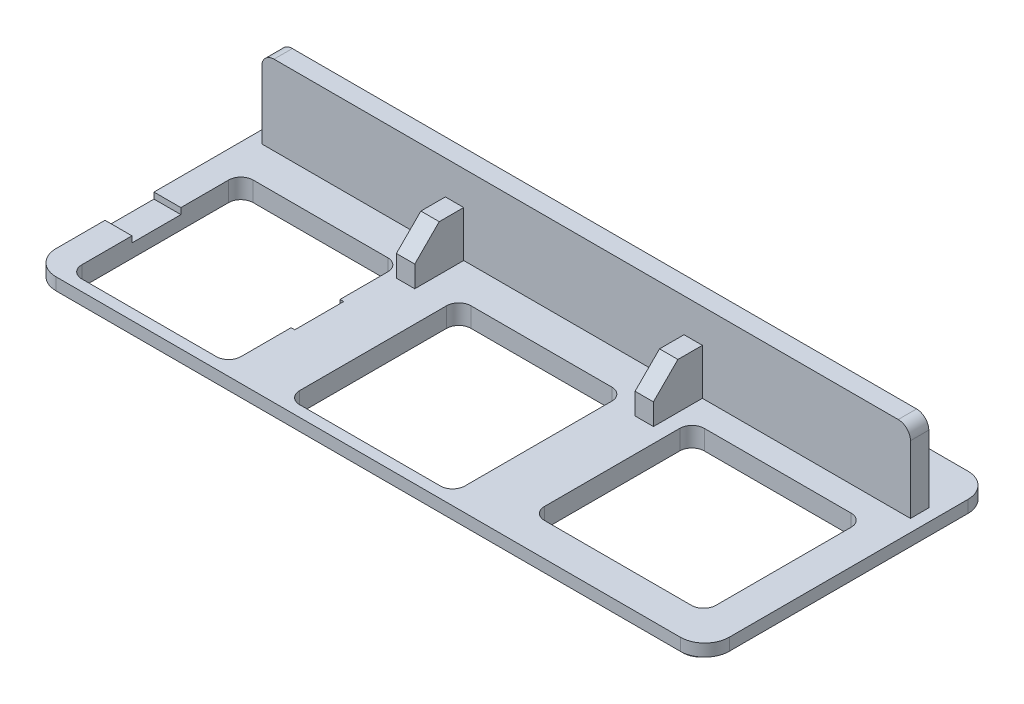
SolidWorks part; units mm, degrees
ref_plane "前视基准面" through (0, 0, 0) normal (0, 0, 1) x (1, 0, 0)
ref_plane "上视基准面" through (0, 0, 0) normal (0, 1, 0) x (1, 0, 0)
ref_plane "右视基准面" through (0, 0, 0) normal (1, 0, 0) x (0, 0, -1)
sketch "草图1" plane through (0, 0, 0) normal (0, 1, 0) x (1, 0, 0)
  line L1 (-27.5, 11.75) -> (27.5, 11.75)
  line L2 (-27.5, 11.75) -> (-27.5, -11.75)
  line L3 (-27.5, -11.75) -> (27.5, -11.75)
  line L4 (27.5, 11.75) -> (27.5, -11.75)
  line L5 (-27.5, 11.75) -> (27.5, -11.75) construction
  line L6 (-27.5, -11.75) -> (27.5, 11.75) construction
  point P0 (0, 0)
  dimension "D1" = 23.5
  dimension "D2" = 55
extrude "凸台-拉伸1" add sketch "草图1" along normal blind 1
fillet "圆角1" radius 2 4 edges at (-27.5, 0.5, 11.75) (27.5, 0.5, 11.75) (-27.5, 0.5, -11.75) (27.5, 0.5, -11.75)
sketch "草图2" plane through (0, 0, 0) normal (0, -1, 0) x (1, 0, 0)
  line L0 (-27.5, -9.75) -> (-27.5, 9.75) construction
  line L1 (-26.6, 11.15) -> (26.6, 11.15)
  line L2 (-26.6, 11.15) -> (-26.6, -11.15)
  line L3 (-26.6, -11.15) -> (26.6, -11.15)
  line L4 (26.6, 11.15) -> (26.6, -11.15)
  line L5 (27.5, 9.75) -> (27.5, -9.75) construction
  line L6 (-25.5, 11.75) -> (25.5, 11.75) construction
  line L7 (25.5, -11.75) -> (-25.5, -11.75) construction
  dimension "D1" = 0.9
  dimension "D2" = 0.9
  dimension "D3" = 0.6
  dimension "D4" = 0.6
extrude "凸台-拉伸2" add sketch "草图2" along normal blind 0.6
sketch "草图3" plane through (0, -0.6, 0) normal (0, -1, 0) x (1, 0, 0)
  line L1 (-25.3, 10.85) -> (-12.3, 10.85)
  line L2 (-25.3, 10.85) -> (-25.3, -3.15)
  line L3 (-25.3, -3.15) -> (-12.3, -3.15)
  line L4 (-12.3, 10.85) -> (-12.3, -3.15)
  line L5 (-7.5, 10.85) -> (6, 10.85)
  line L6 (-7.5, 10.85) -> (-7.5, -3.15)
  line L7 (-7.5, -3.15) -> (6, -3.15)
  line L8 (6, 10.85) -> (6, -3.15)
  line L9 (10.7, 9.0414) -> (24.7, 9.0414)
  line L10 (10.7, 9.0414) -> (10.7, -4.0086)
  line L11 (10.7, -4.0086) -> (24.7, -4.0086)
  line L12 (24.7, 9.0414) -> (24.7, -4.0086)
  line L15 (-27.5, -9.75) -> (-27.5, 9.75) construction
  line L16 (-25.5, 11.75) -> (25.5, 11.75) construction
  line L17 (27.5, 9.75) -> (27.5, -9.75) construction
  dimension "D1" = 13
  dimension "D2" = 13.5
  dimension "D3" = 14
  dimension "D4" = 2.2
  dimension "D5" = 0.9
  dimension "D6" = 20
  dimension "D7" = 13.05
  dimension "D8" = 2.8
  dimension "D10" = 14
extrude "切除-拉伸1" cut sketch "草图3" against normal blind 3
fillet "圆角2" radius 1 12 edges at (-25.3, 0.2, 10.85) (-12.3, 0.2, 10.85) (-7.5, 0.2, 10.85) (6, 0.2, 10.85) (24.7, 0.2, 9.0414) (10.7, 0.2, 9.0414) (24.7, 0.2, -4.0086) (10.7, 0.2, -4.0086) (6, 0.2, -3.15) (-7.5, 0.2, -3.15) (-12.3, 0.2, -3.15) (-25.3, 0.2, -3.15)
sketch "草图4" plane through (0, 1, 0) normal (0, 1, 0) x (1, 0, 0)
  line L0 (-27.5, 9.75) -> (-27.5, -9.75) construction
  line L1 (-12, -5.75) -> (-27.5, -5.75)
  line L2 (-12, -5.75) -> (-12, -1.7526)
  line L3 (-12, -1.7526) -> (-27.5, -1.7526)
  line L4 (-27.5, -5.75) -> (-27.5, -1.7526)
  line L5 (-25.5, -11.75) -> (25.5, -11.75) construction
  dimension "D1" = 6
  dimension "D2" = 3.9974
  dimension "D3" = 15.5
extrude "切除-拉伸2" cut sketch "草图4" against normal blind 0.5
sketch "草图5" plane through (0, 1, 0) normal (0, 1, 0) x (1, 0, 0)
  line L1 (26.5, 6.0546) -> (-26.5, 6.0546)
  line L2 (26.5, 6.0546) -> (26.5, 7.5546)
  line L3 (26.5, 7.5546) -> (-26.5, 7.5546)
  line L4 (-26.5, 6.0546) -> (-26.5, 7.5546)
  line L6 (-27.5, 9.75) -> (-27.5, -1.7526) construction
  line L7 (27.5, -9.75) -> (27.5, 9.75) construction
  line L8 (25.5, 11.75) -> (-25.5, 11.75) construction
  dimension "D1" = 1.5
  dimension "D2" = 1
  dimension "D3" = 1
  dimension "D4" = 4.1954
extrude "凸台-拉伸3" add sketch "草图5" along normal blind 6.5
fillet "圆角3" radius 1 2 edges at (-26.5, 7.5, -6.8046) (26.5, 7.5, -6.8046)
sketch "草图6" plane through (0, 1, 0) normal (0, 1, 0) x (1, 0, 0)
  line L0 (-26.5, 6.0546) -> (26.5, 6.0546) construction
  line L1 (9.5, 6.0546) -> (8, 6.0546)
  line L2 (9.5, 6.0546) -> (9.5, 2.0546)
  line L3 (9.5, 2.0546) -> (8, 2.0546)
  line L4 (8, 6.0546) -> (8, 2.0546)
  line L5 (27.5, -9.75) -> (27.5, 9.75) construction
  line L6 (-10, 6.0546) -> (-11.5, 6.0546)
  line L7 (-10, 6.0546) -> (-10, 2.0546)
  line L8 (-10, 2.0546) -> (-11.5, 2.0546)
  line L9 (-11.5, 6.0546) -> (-11.5, 2.0546)
  line L10 (-27.5, -5.75) -> (-27.5, -9.75) construction
  dimension "D1" = 4
  dimension "D2" = 1.5
  dimension "D3" = 18
  dimension "D4" = 16
extrude "凸台-拉伸4" add sketch "草图6" along normal blind 3.75
chamfer "倒角1" distance 2 angle 45 2 edges at (-10.75, 4.75, -2.0546) (8.75, 4.75, -2.0546)
fillet "圆角4" radius 1.5 4 edges at (-26.6, -0.3, -11.15) (26.6, -0.3, -11.15) (26.6, -0.3, 11.15) (-26.6, -0.3, 11.15)
